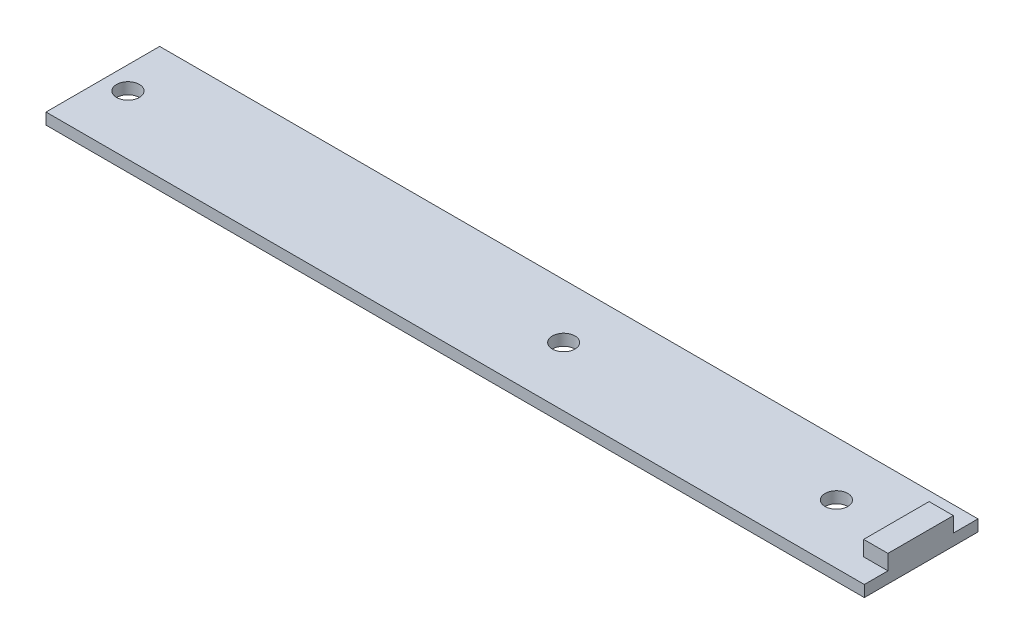
SolidWorks part; units mm, degrees
ref_plane "Front" through (0, 0, 0) normal (0, 0, 1) x (1, 0, 0)
ref_plane "Top" through (0, 0, 0) normal (0, 1, 0) x (1, 0, 0)
ref_plane "Right" through (0, 0, 0) normal (1, 0, 0) x (0, 0, -1)
sketch "Sketch1" plane through (0, 0, 0) normal (0, 1, 0) x (1, 0, 0)
  line L1 (0, 0) -> (108, 0)
  line L2 (0, 0) -> (0, -15)
  line L3 (0, -15) -> (108, -15)
  line L4 (108, 0) -> (108, -15)
  dimension "D1" = 108
  dimension "D2" = 15
extrude "Boss-Extrude1" add sketch "Sketch1" along normal blind 1.5
sketch "Sketch2" plane through (0, 1.5, 0) normal (0, 1, 0) x (1, 0, 0)
  line L0 (108, -15) -> (108, 0) construction
  line L1 (108, -11.8868) -> (104.7971, -11.8868)
  line L2 (108, -11.8868) -> (108, -3.2499)
  line L3 (108, -3.2499) -> (104.7971, -3.2499)
  line L4 (104.7971, -11.8868) -> (104.7971, -3.2499)
extrude "Boss-Extrude2" add sketch "Sketch2" along normal blind 2
sketch "Sketch3" plane through (0, 0, 0) normal (0, -1, 0) x (-1, 0, 0)
  line L0 (0, 0) -> (0, -15) construction
  circle A0 centre (-3, -7.181) radius 1.5
  circle A1 centre (-60.5, -7.181) radius 1.5
  circle A2 centre (-96.5, -7.181) radius 1.5
  dimension "D4" = 3
  dimension "D5" = 3
  dimension "D6" = 3
  dimension "D1" = 57.5
  dimension "D2" = 3
  dimension "D3" = 36
extrude "Cut-Extrude1" cut sketch "Sketch3" against normal blind 2
